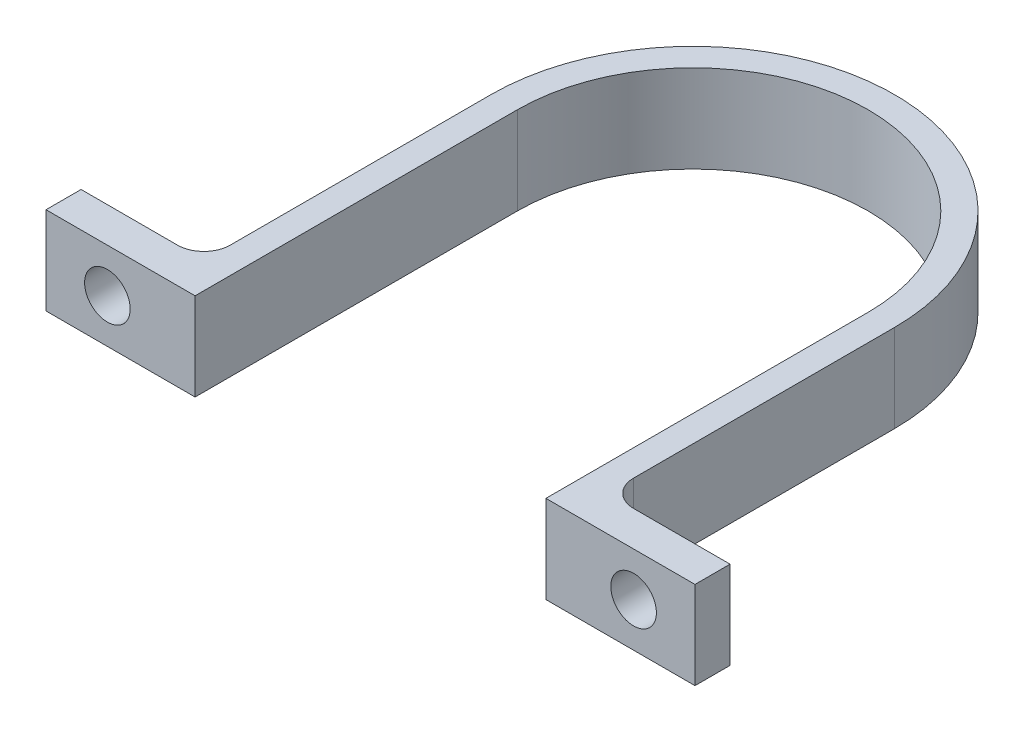
SolidWorks part; units mm, degrees
ref_plane "前视基准面" through (0, 0, 0) normal (0, 0, 1) x (1, 0, 0)
ref_plane "上视基准面" through (0, 0, 0) normal (0, 1, 0) x (1, 0, 0)
ref_plane "右视基准面" through (0, 0, 0) normal (1, 0, 0) x (0, 0, -1)
other "Configuration Table"
sketch "草图1" plane through (0, 0, 0) normal (0, 1, 0) x (1, 0, 0)
  line L0 (-23, 0) -> (-23, -36.75)
  line L1 (23, 0) -> (23, -36.75)
  line L3 (-20, 0) -> (-20, -36.75)
  line L4 (-20, -36.75) -> (-23, -36.75)
  line L5 (20, 0) -> (20, -36.75)
  line L6 (20, -36.75) -> (23, -36.75)
  arc A0 (20, 0) -> (-20, 0) centre (0, 0) ccw
  arc A1 (23, 0) -> (-23, 0) centre (0, 0) ccw
  point P1 (0, 0)
  dimension "D1" = 40
  dimension "D2" = 46
  dimension "D3" = 36.75
extrude "凸台-拉伸1" add sketch "草图1" along normal blind 10
sketch "草图2" plane through (0, 0, 36.75) normal (0, 0, 1) x (1, 0, 0)
  line L0 (0, 21.1607) -> (0, -20.3859) construction
  line L2 (-23, 10) -> (-23, 0) construction
  line L4 (-37, 0) -> (-23, 0)
  line L5 (-37, 0) -> (-37, 10)
  line L6 (-37, 10) -> (-23, 10)
  line L7 (-23, 0) -> (-23, 10)
  line L8 (-37, 0) -> (-23, 10) construction
  line L9 (-37, 10) -> (-23, 0) construction
  line L10 (37, 0) -> (23, 0)
  line L11 (37, 0) -> (37, 10)
  line L12 (37, 10) -> (23, 10)
  line L13 (23, 0) -> (23, 10)
  line L14 (37, 0) -> (23, 10) construction
  line L15 (37, 10) -> (23, 0) construction
  circle A0 centre (-30, 5) radius 2.6
  circle A1 centre (30, 5) radius 2.6
  point P7 (-23, 5)
  dimension "D1" = 5.2
  dimension "D2" = 30
extrude "凸台-拉伸2" add sketch "草图2" against normal blind 4
fillet "圆角1" radius 3 2 edges at (23, 5, 32.75) (-23, 5, 32.75)
